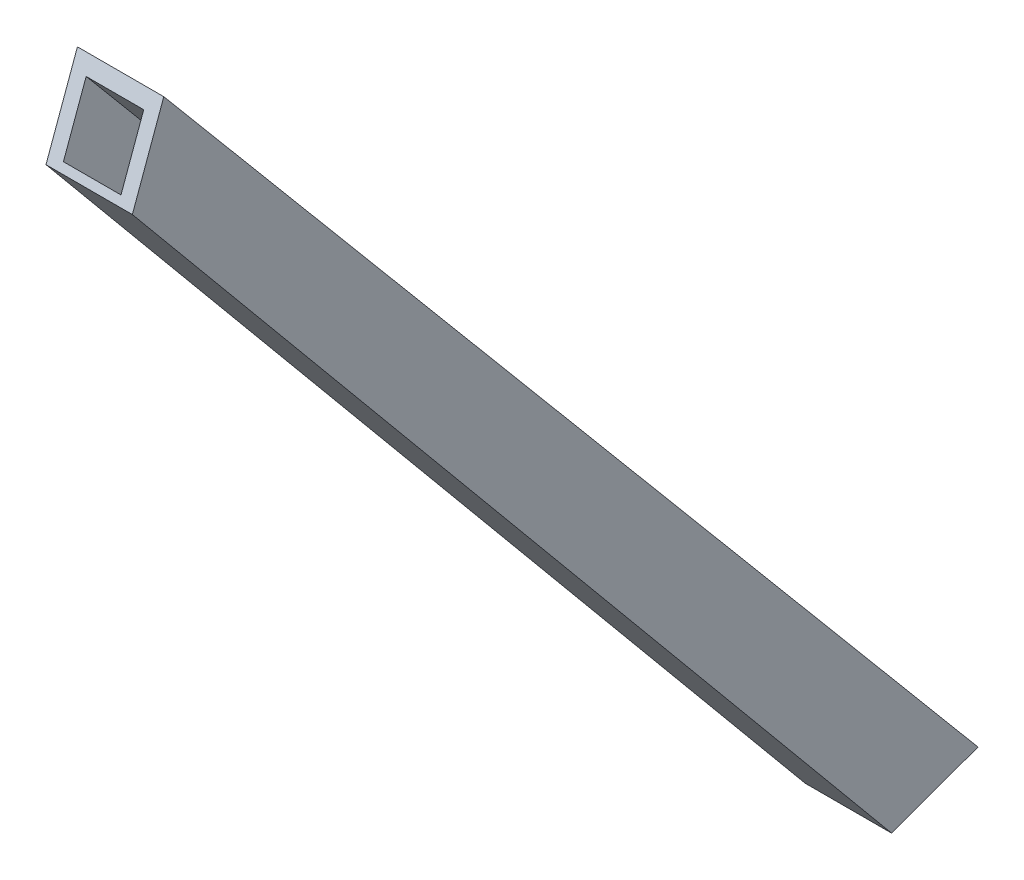
SolidWorks part; units mm, degrees
material "6061 Alloy"
ref_plane "Front Plane" through (0, 0, 0) normal (0, 0, 1) x (1, 0, 0)
ref_plane "Top Plane" through (0, 0, 0) normal (0, 1, 0) x (1, 0, 0)
ref_plane "Right Plane" through (0, 0, 0) normal (1, 0, 0) x (0, 0, -1)
sketch "Sketch1" plane through (0, 0, 0) normal (1, 0, 0) x (0, 0, -1)
  line L0 (249.4449, -198.7415) -> (268.4949, -191.8078)
  line L11 (88.9, 22.225) -> (81.9664, 3.175)
  line L13 (94.61, 15.4201) -> (88.9, 22.225)
  line L14 (94.61, 15.4201) -> (268.4949, -191.8078)
  line L16 (249.4449, -198.7415) -> (81.9664, 3.175)
extrude "Boss-Extrude1" add sketch "Sketch1" along normal blind 19.05
ref_plane "Plane1" through (0, -244.7654, -205.3825) normal (0, -0.766, -0.6428) x (-1, 0, 0)
sketch "Sketch2" plane through (0, -244.7654, -205.3825) normal (0, -0.766, -0.6428) x (-1, 0, 0)
  line L0 (-19.05, 82.3873) -> (0, 82.3873) construction
  line L1 (-3.175, 66.5123) -> (-15.875, 66.5123)
  line L2 (-3.175, 66.5123) -> (-3.175, 79.2123)
  line L3 (-3.175, 79.2123) -> (-15.875, 79.2123)
  line L4 (-15.875, 66.5123) -> (-15.875, 79.2123)
  line L5 (-3.175, 66.5123) -> (-15.875, 79.2123) construction
  line L6 (-3.175, 79.2123) -> (-15.875, 66.5123) construction
  line L7 (-9.525, 82.3873) -> (-9.525, 66.5123) construction
  point P0 (-9.525, 72.8623)
  dimension "D1" = 3.175
  dimension "D2" = 12.7
  dimension "D3" = 12.7
extrude "Cut-Extrude1" cut sketch "Sketch2" against normal through all both and the other way through all
